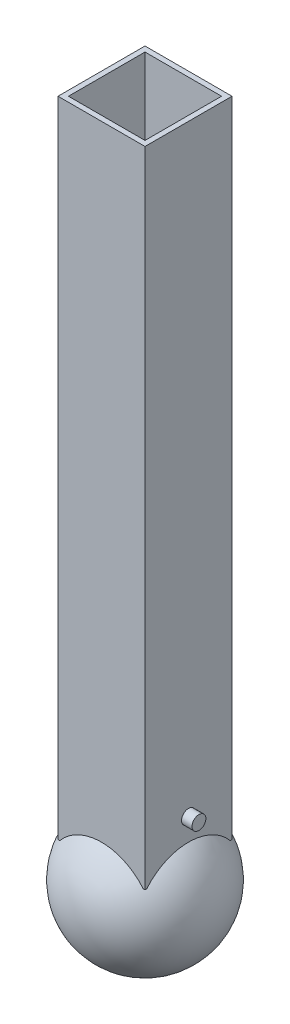
SolidWorks part; units mm, degrees
material "1060 Alloy"
ref_plane "Front Plane" through (0, 0, 0) normal (0, 0, 1) x (1, 0, 0)
ref_plane "Top Plane" through (0, 0, 0) normal (0, 1, 0) x (1, 0, 0)
ref_plane "Right Plane" through (0, 0, 0) normal (1, 0, 0) x (0, 0, -1)
sketch "Sketch1" plane through (0, 0, 0) normal (0, 1, 0) x (1, 0, 0)
  line L0 (0, 56.0843) -> (0, -54.0393) construction
  line L1 (-85.0637, 0) -> (105.2276, 0) construction
  line L3 (-12.5, 12.5) -> (12.5, 12.5)
  line L4 (-12.5, 12.5) -> (-12.5, -12.5)
  line L5 (-12.5, -12.5) -> (12.5, -12.5)
  line L6 (12.5, 12.5) -> (12.5, -12.5)
  line L7 (-12.5, 12.5) -> (12.5, -12.5) construction
  line L8 (-12.5, -12.5) -> (12.5, 12.5) construction
  point P5 (0, 0)
  dimension "D1" = 25
  dimension "D2" = 25
extrude "Boss-Extrude1" add sketch "Sketch1" along normal blind 185
sketch "Sketch3" plane through (0, 0, 0) normal (0, -1, 0) x (1, 0, 0)
  line L0 (0, 13.6526) -> (0, -14.5281) construction
  line L1 (-18.6047, 0) -> (18.7142, 0) construction
  line L4 (-11, 11) -> (11, 11)
  line L5 (-11, 11) -> (-11, -11)
  line L6 (-11, -11) -> (11, -11)
  line L7 (11, 11) -> (11, -11)
  line L8 (-11, 11) -> (11, -11) construction
  line L9 (-11, -11) -> (11, 11) construction
  point P5 (0, 0)
  dimension "D1" = 22
  dimension "D2" = 22
extrude "Cut-Extrude1" cut sketch "Sketch3" against normal blind 300
ref_plane "Plane1" through (0, -10, 0) normal (0, -1, 0) x (-1, 0, 0)
sketch "Sketch4" plane through (0, -10, 0) normal (0, -1, 0) x (-1, 0, 0)
  line L0 (0, 13.2121) -> (0, -13.9344) construction
  line L1 (0, 20) -> (0, -20)
  arc A0 (0, 20) -> (0, -20) centre (0, 0) ccw
  dimension "D2" = 20
  dimension "D1" = 40
revolve "Revolve1" add sketch "Sketch4" angle 360 about L0
sketch "Sketch6" plane through (12.5, 0, 0) normal (1, 0, 0) x (0, 0, -1)
  line L0 (0, 22.0983) -> (0, -32.6766) construction
  line L1 (41.5847, -10) -> (-39.8607, -10) construction
  line L2 (-0.2807, -10) -> (0.2807, -10) construction
  circle A0 centre (0, 12) radius 2
  dimension "D2" = 4
  dimension "D1" = 22
extrude "Cut-Extrude3" cut sketch "Sketch6" against normal blind 25
sketch "Sketch9" plane through (-12.5, 0, 0) normal (-1, 0, 0) x (0, 0, 1)
  circle A0 centre (0, 12) radius 1.99
extrude "Boss-Extrude8" add sketch "Sketch9" against normal blind 28 separate body
sketch "Sketch10" plane through (-12.5, 0, 0) normal (-1, 0, 0) x (0, 0, 1)
  circle A0 centre (0, 12) radius 1.99
extrude "Boss-Extrude9" add sketch "Sketch10" along normal blind 3
